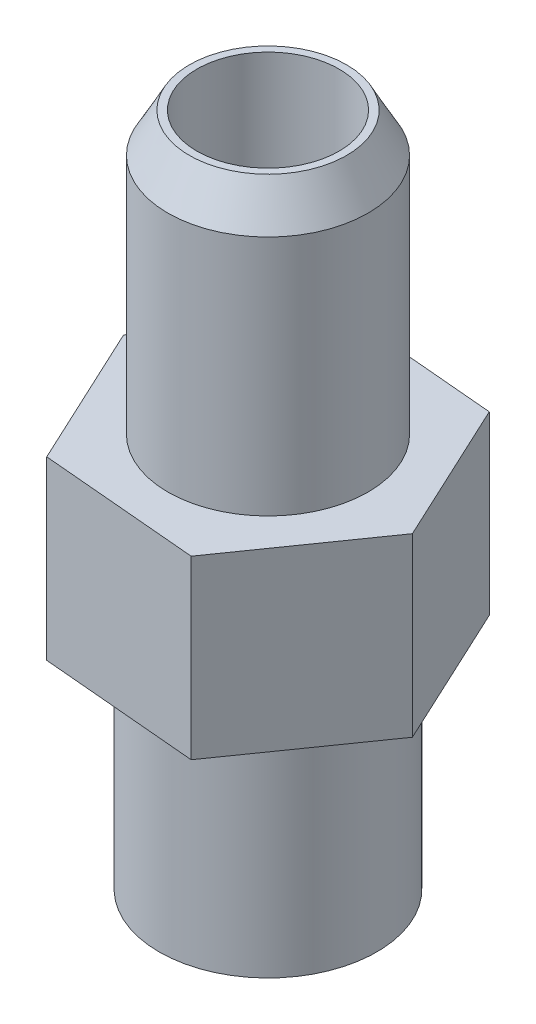
SolidWorks part; units mm, degrees
ref_plane "Front Plane" through (0, 0, 0) normal (0, 0, 1) x (1, 0, 0)
ref_plane "Top Plane" through (0, 0, 0) normal (0, 1, 0) x (1, 0, 0)
ref_plane "Right Plane" through (0, 0, 0) normal (1, 0, 0) x (0, 0, -1)
sketch "Sketch1" plane through (0, 0, 0) normal (0, 0, 1) x (1, 0, 0)
  line L0 (0, 0) -> (0, 31)
  line L1 (0, 0) -> (5, 0)
  line L2 (5, 0) -> (5, 10)
  line L3 (5, 10) -> (6.3, 10)
  line L4 (6.3, 10) -> (6.3, 18.1)
  line L6 (4.6, 18.1) -> (4.6, 29.2)
  line L7 (6.3, 18.1) -> (4.6, 18.1)
  line L8 (4.6, 29.2) -> (3.6112, 31)
  line L9 (3.6112, 31) -> (0, 31)
revolve "Revolve1" add sketch "Sketch1" angle 360 about L0
sketch "Sketch2" plane through (0, 18.1, 0) normal (0, 1, 0) x (1, 0, 0)
  line L1 (7.2715, -0.6366) -> (4.1871, 5.979)
  line L2 (4.1871, 5.979) -> (-3.0844, 6.6156)
  line L3 (-3.0844, 6.6156) -> (-7.2715, 0.6366)
  line L4 (-7.2715, 0.6366) -> (-4.1871, -5.979)
  line L5 (-4.1871, -5.979) -> (3.0844, -6.6156)
  line L6 (3.0844, -6.6156) -> (7.2715, -0.6366)
  circle A0 centre (0, 0) radius 6.3214 construction
extrude "Boss-Extrude1" add sketch "Sketch2" against normal up to surface (8.1 mm away) up to face at (0, 10, -6.3)
sketch "Sketch3" plane through (0, 31, 0) normal (0, 1, 0) x (1, 0, 0)
  circle A0 centre (0, 0) radius 3.2686
extrude "Cut-Extrude1" cut sketch "Sketch3" against normal blind 40
